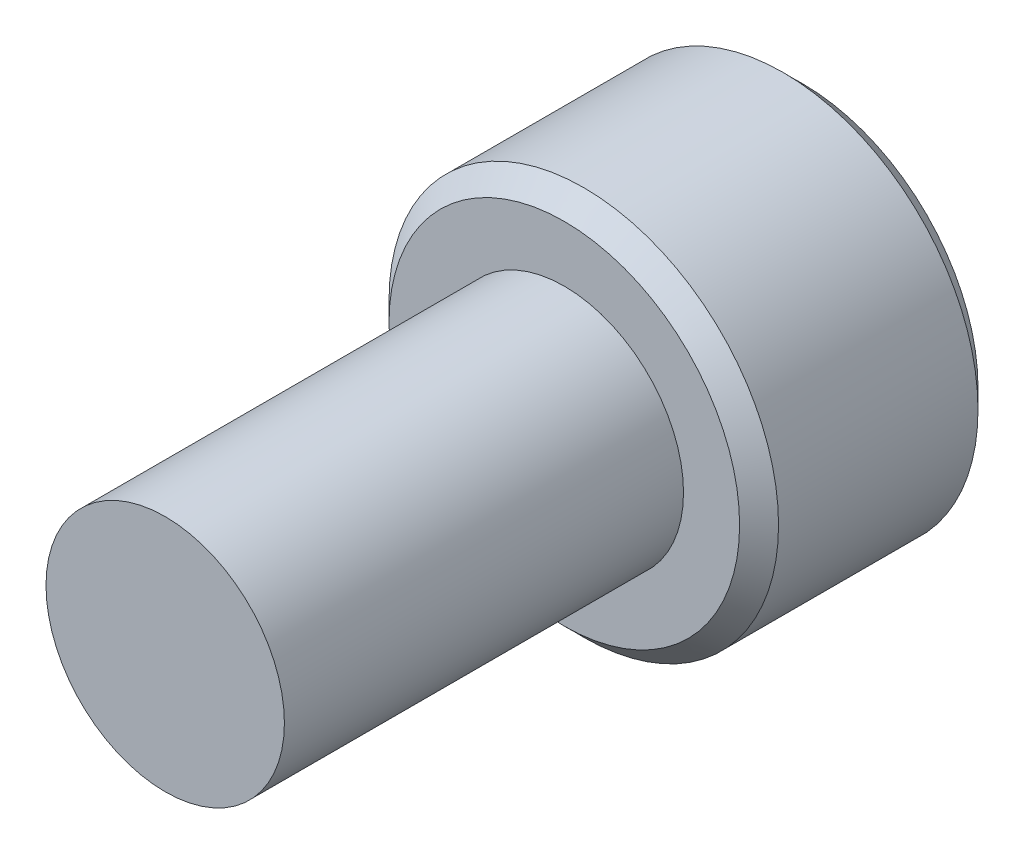
SolidWorks part; units mm, degrees
material "6061 Alloy"
ref_plane "Front Plane" through (0, 0, 0) normal (0, 0, 1) x (1, 0, 0)
ref_plane "Top Plane" through (0, 0, 0) normal (0, 1, 0) x (1, 0, 0)
ref_plane "Right Plane" through (0, 0, 0) normal (1, 0, 0) x (0, 0, -1)
sketch "Sketch1" plane through (0, 0, 0) normal (0, 0, 1) x (1, 0, 0)
  circle A0 centre (0, 0) radius 1.4224
  dimension "OD" = 2.8448
extrude "Extrude1" add sketch "Sketch1" against normal blind 4.7625
sketch "Sketch2" plane through (0, 0, 0) normal (0, 0, 1) x (1, 0, 0)
  circle A0 centre (0, 0) radius 1.4224 construction
  circle A1 centre (0, 0) radius 1.4224
curve "Helix/Spiral1" pitch 0.635 height 5.3975 turns 8.5 parameters "pitch"=0.635
sketch "Sketch3" plane through (0, 0, 0) normal (1, 0, 0) x (0, 0, -1)
  line L0 (-0.5556, 1.4224) -> (-0.3175, 1.01)
  line L1 (-0.3175, 1.01) -> (-0.2381, 1.01)
  line L2 (-0.2381, 1.01) -> (0, 1.4224)
  line L3 (-0.5556, 1.4224) -> (0, 1.4224)
  line L4 (-0.2778, 1.4224) -> (-0.2778, 1.01) construction
  line L5 (-0.4366, 1.2162) -> (-0.1191, 1.2162) construction
  line L6 (0, 1.4224) -> (0, -1.4224) construction
  dimension "D1" = 0.0794
  dimension "D2" = 0.3175
  dimension "D3" = 60
sketch "Sketch4" plane through (0, 0, 0) normal (1, 0, 0) x (0, 0, -1)
  line L0 (0.4666, 1.4224) -> (0, 0.756)
  line L1 (0, 0.756) -> (0, 1.4224)
  line L2 (0.4666, 1.4224) -> (0, 1.4224)
  line L3 (-0.5556, 1.4224) -> (0, 1.4224) construction
  line L4 (0, 0) -> (7.0209, 0) construction
  dimension "D1" = 55
  dimension "D2" = 0.254
sketch "Sketch6" plane through (0, 0, -4.7625) normal (0, 0, -1) x (-1, 0, 0)
  circle A0 centre (0, 0) radius 2.3241
  dimension "head dia" = 4.6482
extrude "Extrude2" add sketch "Sketch6" along normal blind 2.8448
sketch "Sketch7" plane through (0, 0, -7.6073) normal (0, 0, -1) x (-1, 0, 0)
  line L1 (0, 1.3748) -> (-1.1906, 0.6874)
  line L2 (-1.1906, 0.6874) -> (-1.1906, -0.6874)
  line L3 (-1.1906, -0.6874) -> (0, -1.3748)
  line L4 (0, -1.3748) -> (1.1906, -0.6874)
  line L5 (1.1906, -0.6874) -> (1.1906, 0.6874)
  line L6 (1.1906, 0.6874) -> (0, 1.3748)
  circle A0 centre (0, 0) radius 1.1906 construction
  dimension "hex dia" = 2.3813
extrude "Cut-Extrude1" cut sketch "Sketch7" against normal blind 1.7859
sketch "Sketch8" plane through (0, 0, -7.6073) normal (0, 0, -1) x (-1, 0, 0)
  circle A0 centre (0, 0) radius 1.3748
extrude "Cut-Extrude2" cut sketch "Sketch8" against normal through all draft 45
chamfer "Chamfer1" distance 0.2324 angle 45 2 edges at (-2.3241, 0, -7.6073) (-2.3241, 0, -4.7625)
sketch "Sketch10" plane through (0, 0, -4.7625) normal (0, 0, 1) x (1, 0, 0)
  circle A1 centre (0, 0) radius 1.4224
  circle A2 centre (0, 0) radius 1.4224
  dimension "D1" = 0
ref_plane "Plane1" through (0, 0, 0) normal (0, 0, 1) x (1, 0, 0)
extrude "partial thread" [suppressed] add sketch "Sketch10" along normal up to surface (12.7 mm away) separate body
chamfer "Chamfer2" [suppressed] distance 0.0569 angle 45
combine bodies "Combine1" [suppressed] operation type add bodies to combine 107 108
sketch "Sketch9" plane through (0, 0, 0) normal (1, 0, 0) x (0, 0, -1)
  line L0 (0, 1.4224) -> (0, -1.4224) construction
  line L1 (1.5875, 1.4224) -> (1.5875, -1.4224) construction
  dimension "D1" = 1.5875
equation "\"D3@Helix/Spiral1\" = \"screw length@Extrude1\"+\"pitch@Helix/Spiral1\""
equation "\"D1@Sketch3\" = \"pitch@Helix/Spiral1\"*.125"
equation "\"D2@Sketch3\" = \"pitch@Helix/Spiral1\"*.5"
equation "\"D1@Cut-Extrude1\" = \"hex dia@Sketch7\"*.75"
equation "\"D1@Chamfer1\" = \"head dia@Sketch6\"*.05"
equation "\"D1@Sketch9\" = \"pitch@Helix/Spiral1\"*2.5"
equation "\"D1@Chamfer2\"=\"OD@Sketch1\"*.02"
